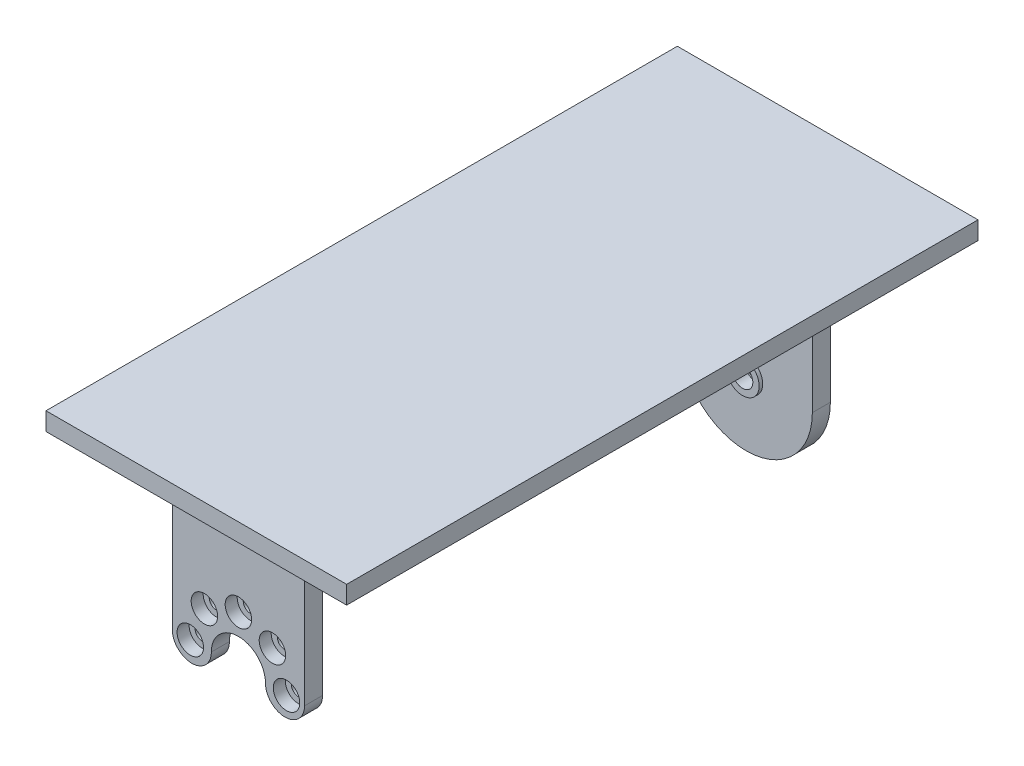
SolidWorks part; units mm, degrees
ref_plane "Plano frontal" through (0, 0, 0) normal (0, 0, 1) x (1, 0, 0)
ref_plane "Plano superior" through (0, 0, 0) normal (0, 1, 0) x (1, 0, 0)
ref_plane "Plano direito" through (0, 0, 0) normal (1, 0, 0) x (0, 0, -1)
sketch "Esboço1" plane through (0, 0, 0) normal (0, 0, 1) x (1, 0, 0)
  line L0 (11, 0) -> (11, 25)
  line L1 (11, 25) -> (-11, 25)
  line L2 (-11, 25) -> (-11, 0)
  arc A3 (11, 0) -> (4.5, 0) centre (7.75, 0) cw
  arc A8 (4.5, 0) -> (-4.5, 0) centre (0, 0) ccw
  arc A10 (-4.5, 0) -> (-11, 0) centre (-7.75, 0) cw
  dimension "D1" = 25
extrude "Ressalto-extrusão1" add sketch "Esboço1" along normal blind 3
sketch "Esboço2" plane through (0, 25, 0) normal (0, 1, 0) x (1, 0, 0)
  line L1 (-25, -10) -> (25, -10)
  line L2 (-25, -10) -> (-25, 95)
  line L3 (-25, 95) -> (25, 95)
  line L4 (25, -10) -> (25, 95)
  line L5 (11, -3) -> (-11, -3) construction
  point P7 (0, -3)
  point P8 (0, -10)
  dimension "D1" = 105
  dimension "D2" = 50
  dimension "D3" = 7
extrude "Ressalto-extrusão2" add sketch "Esboço2" along normal blind 3
ref_plane "Plano1" through (0, 0, -81.45) normal (0, 0, -1) x (-1, 0, 0)
sketch "Esboço3" plane through (0, 0, -81.45) normal (0, 0, -1) x (-1, 0, 0)
  line L1 (-11, 0) -> (-11, 25)
  line L2 (-11, 25) -> (11, 25)
  line L3 (11, 25) -> (11, 0)
  arc A0 (-11, 0) -> (11, 0) centre (0, 0) ccw
  dimension "D1" = 22
extrude "Ressalto-extrusão3" add sketch "Esboço3" along normal blind 3
hole_wizard "Rebaixo para SHCS M21" positions "Esboço4" profile "Esboço5" counterbore size "M2" standard "Ansi Metric"
sketch "Esboço4" plane through (0, 0, 3) normal (0, 0, 1) x (1, 0, 0)
  arc A0 (8.8, 0) -> (7.2, 0) centre (8, 0) ccw construction
  point P0 (8, 0)
sketch "Esboço5" plane through (8, 0, 3) normal (1, 0, 0) x (0, -1, 0)
  line L0 (0, 0) -> (0, 3)
  line L1 (0, 3) -> (1.2, 3)
  line L3 (1.2, 3) -> (1.2, 2)
  line L4 (1.2, 2) -> (2.2, 2)
  line L5 (2.2, 2) -> (2.2, 0)
  line L7 (2.2, 0) -> (0, 0)
  line L11 (0, -6.35) -> (0, 107.95) construction
  dimension "Thru Hole Dia." = 2.4
  dimension "Thru Hole Depth" = 3
  dimension "C'Bore Dia." = 4.4
  dimension "C'Bore Depth" = 2
pattern_circular "PadrãoCircular1" count 5 over 180 about axis through (0, 0, 0) along (0, 0, 1) of "Rebaixo para SHCS M21"
sketch "Esboço6" plane through (0, 0, 0) normal (1, 0, 0) x (0, 0, -1)
  line L0 (-10, 25) -> (-3, 25) construction
  line L3 (-3, 25) -> (-3, 18) construction
  line L4 (-3, 0) -> (-3, 25) construction
  line L5 (-3, 18) -> (-10, 25)
rib "Nervura1" sketch "Esboço6" sketch "Esboço6" thickness 15 extrusion direction parallel to sketch draft on no parameters "D1"=15
sketch "Esboço7" plane through (0, 0, 3) normal (0, 0, 1) x (1, 0, 0)
  line L0 (-7.5, 25) -> (7.5, 25) construction
  line L1 (-5, 25) -> (5, 25)
  line L2 (-5, 25) -> (-5, 18)
  line L3 (-5, 18) -> (5, 18)
  line L4 (5, 25) -> (5, 18)
  line L5 (7.5, 18) -> (-7.5, 18) construction
  point P8 (0, 18)
  point P9 (0, 18)
  dimension "D1" = 10
extrude "Corte-extrusão1" cut sketch "Esboço7" along normal up to surface (7 mm away)
sketch "Esboço8" plane through (0, 0, 0) normal (1, 0, 0) x (0, 0, -1)
  line L0 (0, 18) -> (7, 25)
  line L1 (0, 0) -> (0, 25) construction
  line L2 (-10, 25) -> (95, 25) construction
  line L5 (-10, 25) -> (-3, 18) construction
rib "Nervura7" sketch "Esboço8" sketch "Esboço8" thickness 15 extrusion direction parallel to sketch draft on no parameters "D1"=15
sketch "Esboço9" plane through (0, 0, 0) normal (0, 0, -1) x (-1, 0, 0)
  line L0 (-7.5, 18) -> (7.5, 18) construction
  line L1 (-5, 18) -> (5, 18)
  line L2 (-5, 18) -> (-5, 25)
  line L3 (-5, 25) -> (5, 25)
  line L4 (5, 18) -> (5, 25)
  line L5 (-11, 25) -> (-7.5, 25) construction
  point P8 (0, 18)
  point P9 (0, 18)
  dimension "D1" = 10
extrude "Corte-extrusão2" cut sketch "Esboço9" along normal up to surface up to face at (0, 21.5, -3.5)
pattern_linear "Padrão linear1" count 2 spacing 84.45 along (0, 0, -1) of "Nervura1", "Nervura7", "Corte-extrusão2", "Corte-extrusão1"
sketch "Esboço10" plane through (0, 0, -81.45) normal (0, 0, 1) x (1, 0, 0)
  circle A0 centre (0, 0) radius 2.75
  circle A2 centre (0, 0) radius 3.25 construction
  dimension "D1" = 0.5
extrude "Ressalto-extrusão4" add sketch "Esboço10" along normal offset from surface (0.6 mm away) 0.25 contours A0
hole_wizard "Rebaixo para parafuso com cabeça panela de M31" positions "Esboço11" profile "Esboço12" counterbore size "M3" standard "DIN" end condition up to next
sketch "Esboço11" plane through (0, 0, -84.45) normal (0, 0, -1) x (-1, 0, 0)
  circle A0 centre (0, 0) radius 3.25 construction
  point P0 (0, 0)
sketch "Esboço12" plane through (0, 0, -84.45) normal (1, 0, 0) x (0, 1, 0)
  line L0 (0, 0) -> (0, 3.6)
  line L1 (0, 3.6) -> (1.7, 3.6)
  line L3 (1.7, 3.6) -> (1.7, 1.5)
  line L4 (1.7, 1.5) -> (3.5, 1.5)
  line L5 (3.5, 1.5) -> (3.5, 0)
  line L7 (3.5, 0) -> (0, 0)
  line L11 (0, -6.35) -> (0, 107.95) construction
  dimension "Thru Hole Dia." = 3.4
  dimension "Thru Hole Depth" = 3.6
  dimension "C'Bore Dia." = 7
  dimension "C'Bore Depth" = 1.5
fillet "Filete1" radius 5 16 edges at (-11, 25, -82.95) (-9.25, 25, -81.45) (-9.25, 25, -84.45) (0, 25, -84.45) (0, 25, -81.45) (9.25, 25, -81.45) (11, 25, -82.95) (9.25, 25, -84.45) (-9.25, 25, 0) (-9.25, 25, 3) (9.25, 25, 3) (9.25, 25, 0) (11, 25, 1.5) (-11, 25, 1.5) (0, 25, 0) (0, 25, 3)
